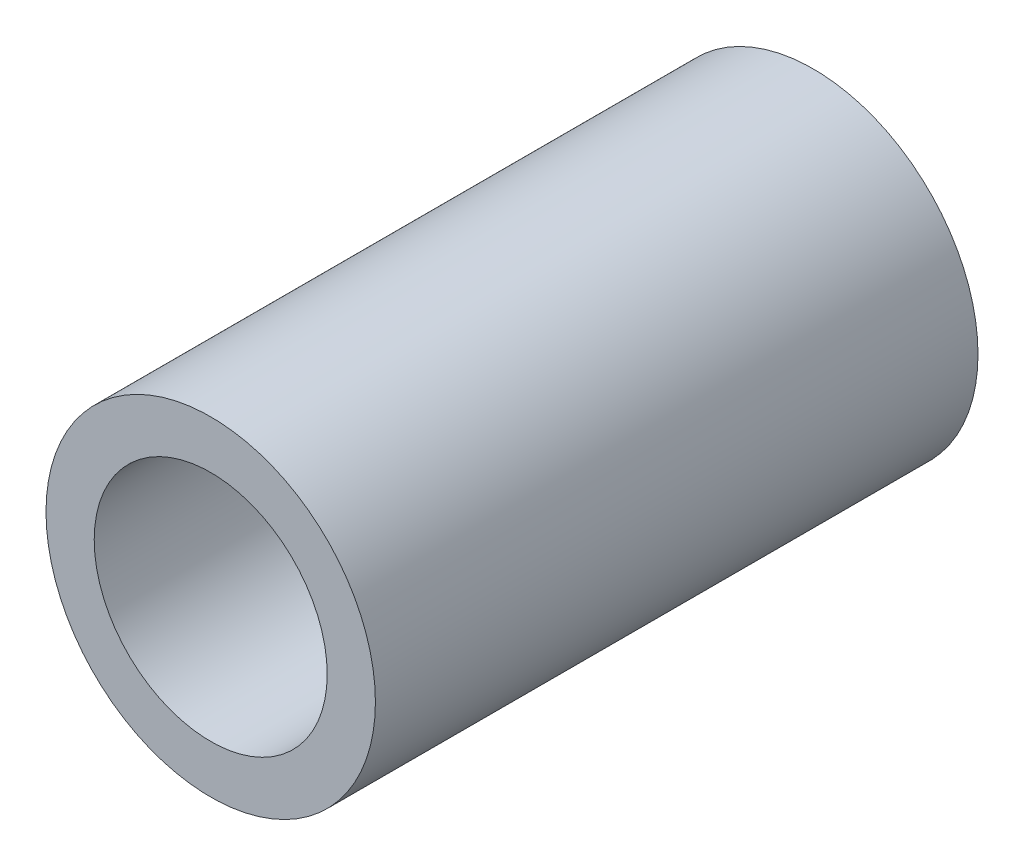
SolidWorks part; units mm, degrees
ref_plane "Front Plane" through (0, 0, 0) normal (0, 0, 1) x (1, 0, 0)
ref_plane "Top Plane" through (0, 0, 0) normal (0, 1, 0) x (1, 0, 0)
ref_plane "Right Plane" through (0, 0, 0) normal (1, 0, 0) x (0, 0, -1)
sketch "Sketch1" plane through (0, 0, 0) normal (0, 0, 1) x (1, 0, 0)
  circle A0 centre (0, 0) radius 1.45
  circle A1 centre (0, 0) radius 2.05
  dimension "D1" = 0.6
  dimension "D2" = 4.1
extrude "Boss-Extrude1" add sketch "Sketch1" along normal blind 7.5
